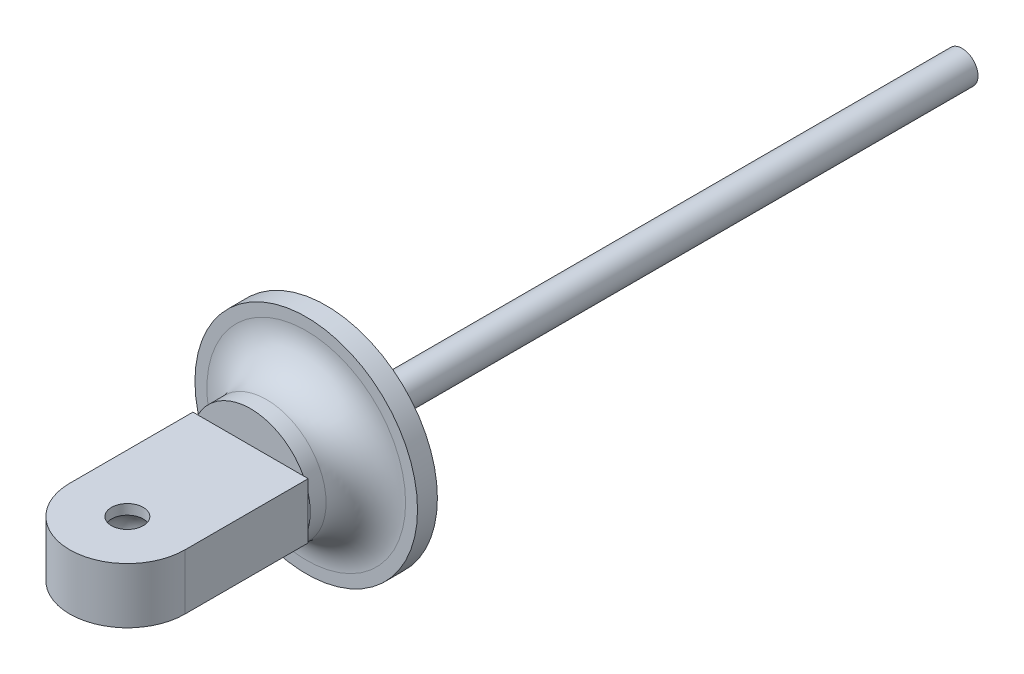
SolidWorks part; units mm, degrees
ref_plane "前视基准面" through (0, 0, 0) normal (0, 0, 1) x (1, 0, 0)
ref_plane "上视基准面" through (0, 0, 0) normal (0, 1, 0) x (1, 0, 0)
ref_plane "右视基准面" through (0, 0, 0) normal (1, 0, 0) x (0, 0, -1)
sketch "草图1" plane through (0, 0, 0) normal (0, 0, 1) x (1, 0, 0)
  circle A0 centre (0, 0) radius 2
  dimension "D1" = 4
extrude "凸台-拉伸1" add sketch "草图1" along normal blind 80
sketch "草图2" plane through (0, 0, 80) normal (0, 0, 1) x (1, 0, 0)
  circle A0 centre (0, 0) radius 14
  dimension "D1" = 28
extrude "凸台-拉伸2" add sketch "草图2" along normal blind 2.5
sketch "草图3" plane through (0, 0, 82.5) normal (0, 0, 1) x (1, 0, 0)
  circle A0 centre (0, 0) radius 7.5
  circle A1 centre (0, 0) radius 14
  circle A2 centre (0, 0) radius 14 construction
  dimension "D2" = 15
  dimension "D1" = 0
extrude "凸台-拉伸3" add sketch "草图3" along normal blind 7
sketch "草图4" plane through (0, 0, 0) normal (0, 1, 0) x (1, 0, 0)
  line L0 (7.25, -105) -> (7.25, -89.5)
  line L1 (-7.5, -89.5) -> (7.5, -89.5) construction
  line L2 (-7.25, -105) -> (-7.25, -89.5)
  line L3 (-7.25, -89.5) -> (7.25, -89.5)
  line L5 (14, -80) -> (-14, -80) construction
  circle A0 centre (0, -105) radius 7.25
  dimension "D1" = 14.5
  dimension "D2" = 25
fillet "圆角1" radius 5 1 edges at (7.5, 0, 82.5)
extrude "凸台-拉伸4" add sketch "草图4" along normal mid plane 7 contours A0 L0 L3 L2 | A0
sketch "草图5" plane through (0, -3.5, 0) normal (0, -1, 0) x (1, 0, 0)
  circle A0 centre (0, 105) radius 2
  dimension "D1" = 4
extrude "切除-拉伸1" cut sketch "草图5" against normal blind 7
sketch "草图6" plane through (0, 0, 0) normal (0, 1, 0) x (1, 0, 0)
  line L0 (0, -112.25) -> (0, -96.2105) construction
  line L1 (0, -102) -> (0, -108)
  arc A0 (-7.25, -105) -> (7.25, -105) centre (0, -105) ccw construction
  arc A1 (0, -108) -> (0, -102) centre (0, -105) ccw
  dimension "D1" = 6
revolve "切除-旋转1" cut sketch "草图6" angle 360 about L0
